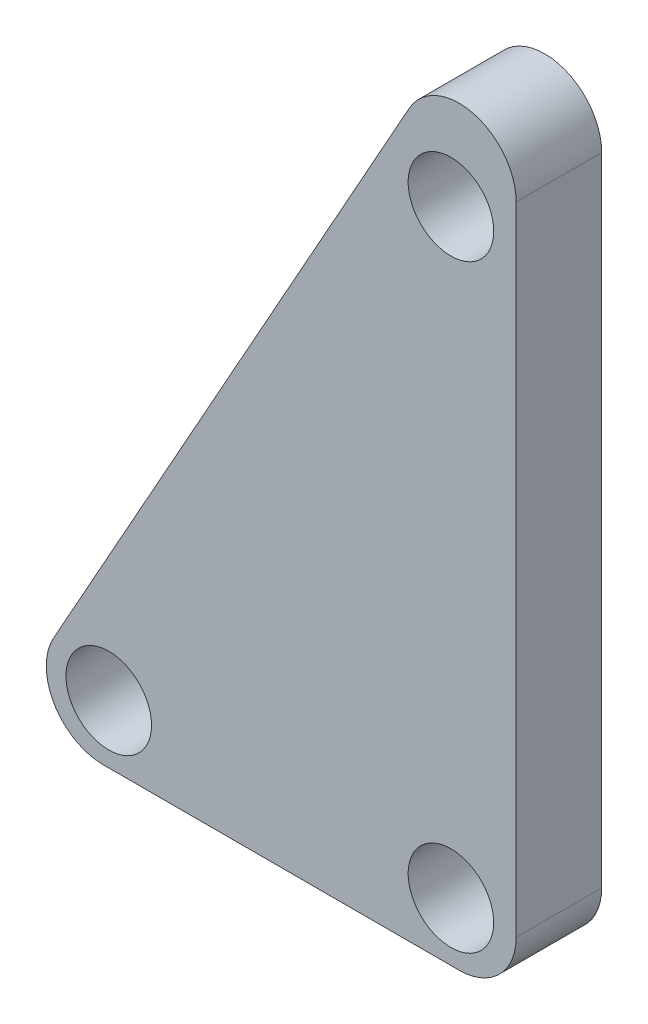
SolidWorks part; units mm, degrees
ref_plane "Front Plane" through (0, 0, 0) normal (0, 0, 1) x (1, 0, 0)
ref_plane "Top Plane" through (0, 0, 0) normal (0, 1, 0) x (1, 0, 0)
ref_plane "Right Plane" through (0, 0, 0) normal (1, 0, 0) x (0, 0, -1)
sketch "Sketch1" plane through (0, 0, 0) normal (0, 0, 1) x (1, 0, 0)
  line L0 (-20, 0) -> (-144.7833, 0)
  line L1 (55, 0) -> (-55, 0) construction
  line L2 (-162.2431, 29.7549) -> (-37.4597, 253.0971)
  line L3 (0, -55) -> (0, 55) construction
  line L4 (0, 243.3421) -> (0, 20)
  circle A0 centre (-22.8789, 230.4635) radius 15
  circle A1 centre (-22.8789, 20.4635) radius 15
  circle A2 centre (-142.8789, 20.4635) radius 15
  arc A3 (-37.4597, 253.0971) -> (0, 243.3421) centre (-20, 243.3421) cw
  arc A4 (-20, 0) -> (0, 20) centre (-20, 20) ccw
  arc A5 (-144.7833, 0) -> (-162.2431, 29.7549) centre (-144.7833, 20) cw
  point P16 (0, 320.1439)
  point P19 (0, 0)
  point P22 (-178.8674, 0)
  point P23 (-144.7833, 0)
  point P24 (0, 230.4635)
  point P25 (0, 0)
  point P26 (0, 243.3421)
  dimension "D1" = 30
  dimension "D2" = 30
  dimension "D3" = 30
  dimension "D6" = 20
  dimension "D4" = 210
  dimension "D5" = 120
extrude "Boss-Extrude1" add sketch "Sketch1" along normal blind 30
